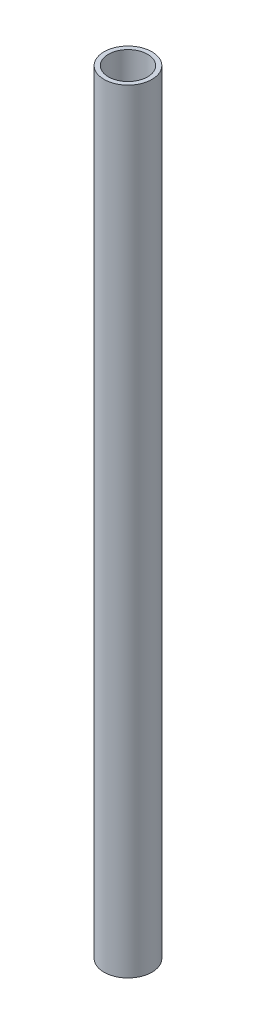
SolidWorks part; units mm, degrees
ref_plane "Спереди" through (0, 0, 0) normal (0, 0, 1) x (1, 0, 0)
ref_plane "Сверху" through (0, 0, 0) normal (0, 1, 0) x (1, 0, 0)
ref_plane "Справа" through (0, 0, 0) normal (1, 0, 0) x (0, 0, -1)
sketch "Эскиз1" plane through (0, 0, 0) normal (0, 1, 0) x (1, 0, 0)
  line L0 (13, 0) -> (42.4504, 0) construction
  circle A0 centre (0, 0) radius 9
  circle A1 centre (0, 0) radius 11
extrude "Вытянуть1" add sketch "Эскиз1" along normal blind 355
